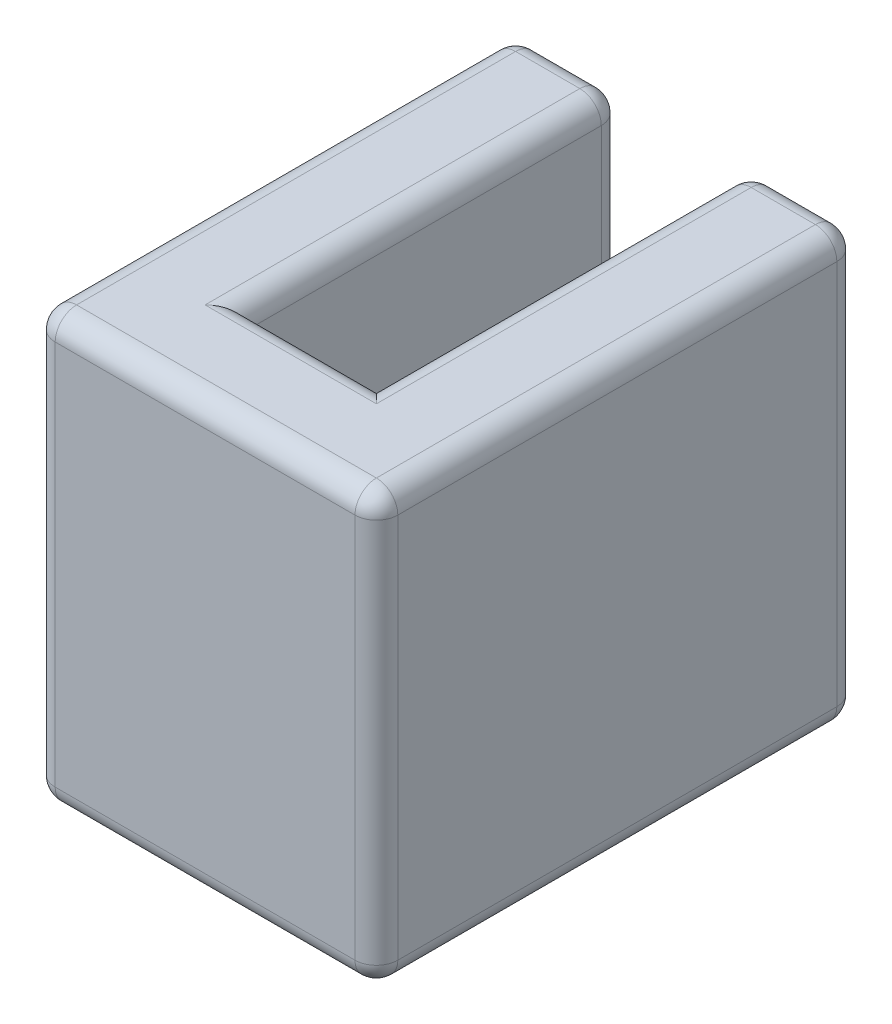
SolidWorks part; units mm, degrees
ref_plane "Front Plane" through (0, 0, 0) normal (0, 0, 1) x (1, 0, 0)
ref_plane "Top Plane" through (0, 0, 0) normal (0, 1, 0) x (1, 0, 0)
ref_plane "Right Plane" through (0, 0, 0) normal (1, 0, 0) x (0, 0, -1)
sketch "Sketch1" plane through (0, 0, 0) normal (0, 1, 0) x (1, 0, 0)
  line L0 (0, 0) -> (-6.4, 0)
  line L1 (-6.4, 0) -> (-6.4, 9)
  line L2 (-6.4, 9) -> (-4.4, 9)
  line L3 (-4.4, 9) -> (-4.4, 2)
  line L4 (-4.4, 2) -> (-2, 2)
  line L5 (-2, 2) -> (-2, 9)
  line L6 (-2, 9) -> (0, 9)
  line L7 (0, 9) -> (0, 0)
  dimension "D1" = 2.4
  dimension "D2" = 2
  dimension "D3" = 7
  dimension "D4" = 9
extrude "Boss-Extrude1" add sketch "Sketch1" along normal blind 8
fillet "Fillet1" radius 0.4 22 edges at (-2, 0, -5.5) (-3.2, 0, -2) (-4.4, 0, -5.5) (-6.4, 0, -4.5) (-4.4, 4, -9) (-6.4, 4, -9) (-5.4, 0, -9) (-2, 4, -9) (-1, 0, -9) (0, 4, -9) (0, 0, -4.5) (-6.4, 4, 0) (0, 4, 0) (-3.2, 0, 0) (-3.2, 8, 0) (-6.4, 8, -4.5) (-5.4, 8, -9) (-4.4, 8, -5.5) (-3.2, 8, -2) (-2, 8, -5.5) (-1, 8, -9) (0, 8, -4.5)
